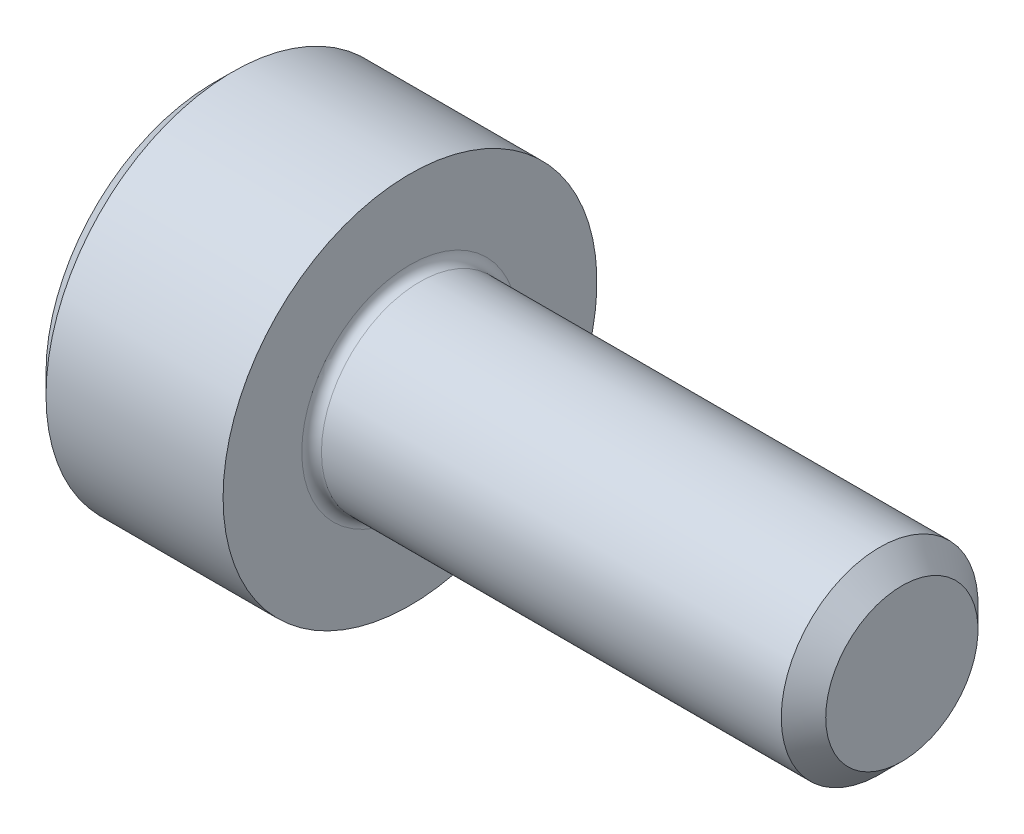
SolidWorks part; units mm, degrees
ref_plane "Plane1" through (0, 0, 0) normal (0, 0, 1) x (1, 0, 0)
ref_plane "Plane2" through (0, 0, 0) normal (0, 1, 0) x (1, 0, 0)
ref_plane "Plane3" through (0, 0, 0) normal (1, 0, 0) x (0, 0, -1)
sketch "BodySke" plane through (0, 0, 0) normal (0, 0, 1) x (1, 0, 0)
  line L0 (0, 0) -> (0, 1.7)
  line L1 (0.2, 1.9) -> (2, 1.9)
  line L2 (2, 1.9) -> (2, 1)
  line L3 (2, 1) -> (6.774, 1)
  line L4 (7, 0.774) -> (7, 0)
  line L5 (7, 0) -> (0, 0)
  line L6 (-31.75, 0) -> (127, 0) construction
  line L7 (0, 1.7) -> (0.2, 1.9)
  line L8 (7, 0.774) -> (6.774, 1)
  line L9 (0, -1.7) -> (0.2, -1.9) construction
  line L10 (7, -0.774) -> (6.774, -1) construction
  line L11 (2.4, 9.525) -> (2.4, 3.175) construction
  line L12 (2, 9.525) -> (2, 3.175) construction
  line L13 (-43, 9.525) -> (-43, 3.175) construction
  dimension "Diameter" = 2
  dimension "Head_ht" = 2
  dimension "Length" = 5
  dimension "Body_ch_ang" = 45
  dimension "Head_dia" = 3.8
  dimension "Head_ch_ang" = 45
  dimension "Minor_dia" = 1.548
  dimension "Advance" = 0.4
  dimension "Thread_nom" = 5
  dimension "Thread_length" = 50
  dimension "Head_ch_ht" = 0.2
revolve "Base-Revolve" add sketch "BodySke"
cosmetic thread "ThreadCosmetic" [suppressed]
fillet "Fillet1" radius 0.1 1 edges at (2, 0, 1)
sketch "Sketch2" plane through (0, 0, 0) normal (0, 0, 1) x (1, 0, 0)
  line L0 (0, 0.7725) -> (1, 0.7725)
  line L1 (1, 0.7725) -> (1.446, 0)
  line L2 (-31.75, 0) -> (127, 0) construction
  line L3 (1.446, 0) -> (0, 0)
  line L4 (0, 0) -> (0, 0.7725)
  line L5 (0, 1.7) -> (0, -1.7) construction
  line L6 (0, 0) -> (47.625, 0) construction
  line L7 (2, -1.9) -> (2, 1.9) construction
  dimension "D1" = 0.7725
  dimension "D2" = 60
  dimension "Wall_thickness" = 1
revolve "Hex-PreBroach" cut sketch "Sketch2" angle 360 about L6
sketch "Sketch3" plane through (0, 0, 0) normal (-1, 0, 0) x (0, 0.5, 0.866)
  line L0 (0.446, 0.7725) -> (-0.446, 0.7725)
  line L1 (-0.446, 0.7725) -> (-0.892, 0)
  line L2 (0.446, 0.7725) -> (0.892, 0)
  line L3 (0.446, -0.7725) -> (0.892, 0)
  line L4 (0.446, -0.7725) -> (-0.446, -0.7725)
  line L5 (-0.446, -0.7725) -> (-0.892, 0)
  dimension "D1" = 0.7725
  dimension "D2" = 0.7725
  dimension "Hex_size" = 1.545
extrude "Hex" cut sketch "Sketch3" against normal blind 1
sketch "Sketch4" plane through (0, 0, 0) normal (-1, 0, 0) x (0, 0, 1)
  line L0 (0, 0) -> (0.9398, 0)
  line L1 (0, 0) -> (6.1484, 3.5498) construction
  line L2 (0, 0) -> (0.4699, 0.8139)
  line L3 (0.7832, 0.2175) -> (0.8962, 0.2828)
  line L4 (0.58, 0.5695) -> (0.693, 0.6348)
  arc A0 (0.7832, 0.2175) -> (0.58, 0.5695) centre (0, 0) ccw
  arc A1 (0.9398, 0) -> (0.8962, 0.2828) centre (0, 0) ccw
  arc A2 (0.4699, 0.8139) -> (0.693, 0.6348) centre (0, 0) cw
  dimension "D1" = 30
  dimension "Spline_n_dim" = 1.6256
  dimension "Spline_m_dim" = 1.8796
  dimension "D2" = 60
  dimension "D3" = 0.2032
  dimension "Spline_p_dim" = 0.4064
extrude "Spline" [suppressed] cut sketch "Sketch4" against normal blind 1
pattern_circular "CirPattern1" [suppressed] count 6 every 60
sketch "Sketch5" plane through (0, 0, 0) normal (0, 0, 1) x (1, 0, 0)
  line L0 (-31.75, 0) -> (127, 0) construction
  line L2 (0, 1.7) -> (0, -1.7) construction
  circle A0 centre (0.1, 0) radius 0.005
  dimension "Drilled_hole_dia" = 0.01
  dimension "Drilled_hole_loc" = 0.1
extrude "Hole" [suppressed] cut sketch "Sketch5" against normal through all and the other way through all
pattern_circular "Drilled-4" [suppressed] count 2 every 60
pattern_circular "Drilled-6" [suppressed] count 3 every 60
sketch "ThdSchSke" plane through (0, 0, 0) normal (0, 0, 1) x (1, 0, 0)
  line L0 (2.4, -0.774) -> (2.2418, -1)
  line L1 (2.4, -0.774) -> (2.5582, -1)
  line L2 (2.5582, -1) -> (2.5582, -1.25)
  line L3 (-3.175, 0) -> (5.1513, 0) construction
  line L5 (2.5582, -1.25) -> (2.2418, -1.25)
  line L6 (2.2418, -1.25) -> (2.2418, -1)
  line L7 (0, 1.7) -> (0, -1.7) construction
  dimension "Thread_minor" = 1.548
  dimension "Diameter" = 2
  dimension "Start" = 2.4
  dimension "SideAngle" = 55
  dimension "VeeAngle" = 70
  dimension "Overcut" = 2.5
revolve "ThreadSchematic" [suppressed] cut sketch "ThdSchSke" angle 360 about L3
pattern_linear "ThdSchPat" [suppressed]
equation "\"D2@Sketch3\" = \"Hex_size@Sketch3\" / 2"
equation "\"D1@Sketch3\" = \"Hex_size@Sketch3\" / 2"
equation "\"D1@Sketch2\" = \"Hex_size@Sketch3\" / 2"
equation "\"D3@Sketch4\" = \"Spline_p_dim@Sketch4\" / 2"
equation "\"Thread_minor@ThreadCosmetic\"  =  \"Minor_dia@BodySke\""
equation "\"D2@CirPattern1\" = 360 / \"Num_teeth@CirPattern1\""
equation "\"Wall_thickness@Sketch2\" = \"Head_ht@BodySke\" - \"Key_eng@Hex\""
equation "\"Thread_length@ThreadCosmetic\" = ((sgn( (\"Length@BodySke\" - \"Advance@BodySke\" ) - \"Thread_nom@BodySke\" )-1)*( (\"Length@BodySke\" - \"Advance@BodySke\" ) - \"Thread_nom@BodySke\" ))/-2+ \"Thread_nom@BodySke\""
equation "\"Thread_minor@ThdSchSke\" = \"Minor_dia@BodySke\""
equation "\"Diameter@ThdSchSke\" = \"Diameter@BodySke\""
equation "\"Overcut@ThdSchSke\" = \"Diameter@BodySke\" * 1.25"
equation "\"Start@ThdSchSke\" = \"Head_ht@BodySke\" + \"Length@BodySke\" - \"Thread_length@ThreadCosmetic\"  '---Non-countersunk---"
equation "\"Num_threads@ThdSchPat\" = int( \"Thread_length@ThreadCosmetic\" / \"Advance@BodySke\" + 0.999 )  + 1"
equation "\"Advance@ThdSchPat\" = \"Thread_length@ThreadCosmetic\" /  (\"Num_threads@ThdSchPat\" - 1) 'relax it"
equation "\"Num_threads@ThdSchPat\" = \"Num_threads@ThdSchPat\" - sgn( \"Num_threads@ThdSchPat\" - 1) '---chamfered tips only---"
